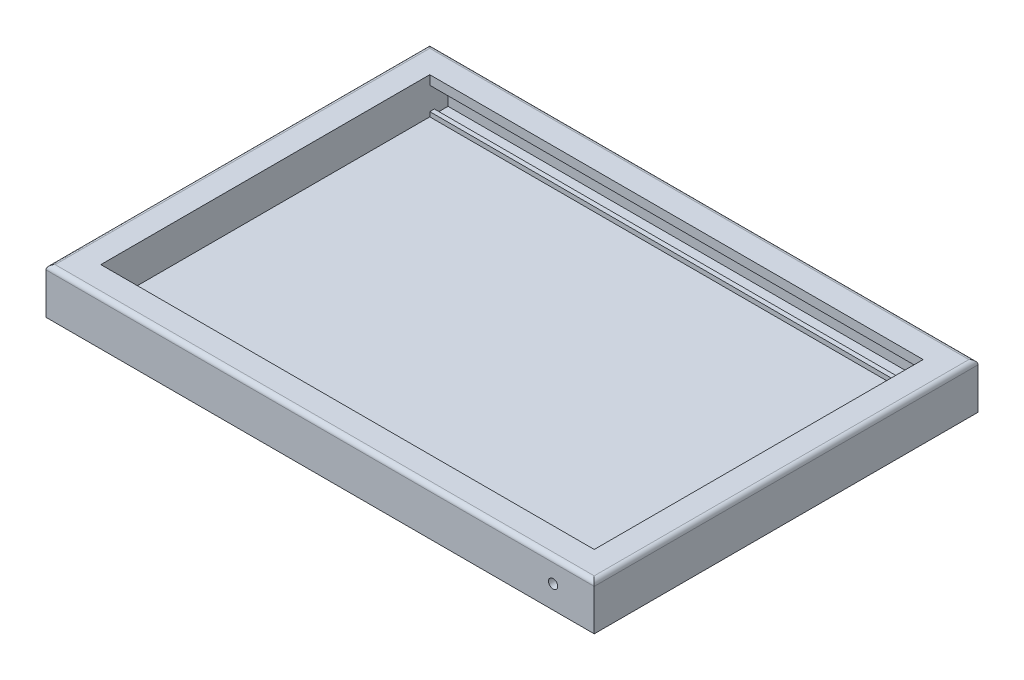
SolidWorks part; units mm, degrees
ref_plane "정면" through (0, 0, 0) normal (0, 0, 1) x (1, 0, 0)
ref_plane "윗면" through (0, 0, 0) normal (0, 1, 0) x (1, 0, 0)
ref_plane "우측면" through (0, 0, 0) normal (1, 0, 0) x (0, 0, -1)
sketch "스케치1" plane through (0, 0, 0) normal (0, 1, 0) x (1, 0, 0)
  line L1 (-571.2787, 18) -> (28.7213, 18)
  line L2 (-571.2787, 18) -> (-571.2787, -402)
  line L3 (-571.2787, -402) -> (28.7213, -402)
  line L4 (28.7213, 18) -> (28.7213, -402)
  dimension "D1" = 600
  dimension "D2" = 420
extrude "보스-돌출1" add sketch "스케치1" along normal blind 50
sketch "스케치2" plane through (0, 50, 0) normal (0, 1, 0) x (1, 0, 0)
  line L0 (28.7213, 18) -> (-571.2787, 18) construction
  line L1 (-541.2787, -12) -> (-1.2787, -12)
  line L2 (-541.2787, -12) -> (-541.2787, -372)
  line L3 (-541.2787, -372) -> (-1.2787, -372)
  line L4 (-1.2787, -12) -> (-1.2787, -372)
  line L5 (-571.2787, 18) -> (-571.2787, -402) construction
  line L6 (-571.2787, -402) -> (28.7213, -402) construction
  line L7 (28.7213, -402) -> (28.7213, 18) construction
  dimension "D1" = 30
  dimension "D2" = 30
  dimension "D3" = 30
  dimension "D4" = 30
extrude "컷-돌출1" cut sketch "스케치2" against normal blind 40
sketch "스케치3" plane through (0, 0, 12) normal (0, 0, 1) x (1, 0, 0)
  line L0 (-1.2787, 50) -> (-541.2787, 50) construction
  line L1 (-541.2787, 10) -> (-1.2787, 10)
  line L2 (-541.2787, 10) -> (-541.2787, 40)
  line L3 (-541.2787, 40) -> (-1.2787, 40)
  line L4 (-1.2787, 10) -> (-1.2787, 40)
  line L5 (-1.2787, 10) -> (-1.2787, 50) construction
  dimension "D1" = 10
extrude "컷-돌출2" cut sketch "스케치3" against normal blind 20
sketch "스케치4" plane through (0, 0, 372) normal (0, 0, -1) x (-1, 0, 0)
  line L0 (541.2787, 10) -> (541.2787, 50) construction
  line L1 (1.2787, 10) -> (541.2787, 10)
  line L2 (1.2787, 10) -> (1.2787, 40)
  line L3 (1.2787, 40) -> (541.2787, 40)
  line L4 (541.2787, 10) -> (541.2787, 40)
  line L5 (541.2787, 50) -> (1.2787, 50) construction
  dimension "D1" = 10
extrude "컷-돌출3" cut sketch "스케치4" against normal blind 20
sketch "스케치6" plane through (0, 50, 0) normal (0, 1, 0) x (1, 0, 0)
  line L0 (-1.2787, -12) -> (-541.2787, -12) construction
  line L1 (-1.2787, -12) -> (-541.2787, -12)
  line L2 (-1.2787, -12) -> (-1.2787, -7)
  line L3 (-1.2787, -7) -> (-541.2787, -7)
  line L4 (-541.2787, -12) -> (-541.2787, -7)
  dimension "D1" = 5
extrude "보스-돌출3" add sketch "스케치6" against normal blind 40
sketch "스케치7" plane through (0, 50, 0) normal (0, 1, 0) x (1, 0, 0)
  line L1 (-1.2787, -372) -> (-541.2787, -372)
  line L2 (-1.2787, -372) -> (-1.2787, -377)
  line L3 (-1.2787, -377) -> (-541.2787, -377)
  line L4 (-541.2787, -372) -> (-541.2787, -377)
  dimension "D1" = 5
extrude "보스-돌출4" add sketch "스케치7" against normal blind 40
sketch "스케치8" plane through (0, 0, 372) normal (0, 0, -1) x (-1, 0, 0)
  line L0 (1.2787, 10) -> (1.2787, 50) construction
  line L1 (1.2787, 45) -> (541.2787, 45)
  line L2 (1.2787, 45) -> (1.2787, 15)
  line L3 (1.2787, 15) -> (541.2787, 15)
  line L4 (541.2787, 45) -> (541.2787, 15)
  line L5 (541.2787, 50) -> (1.2787, 50) construction
  line L6 (1.2787, 10) -> (541.2787, 10) construction
  dimension "D1" = 5
  dimension "D2" = 5
  dimension "D3" = 540
extrude "컷-돌출4" cut sketch "스케치8" against normal blind 20
sketch "스케치9" plane through (0, 0, 12) normal (0, 0, 1) x (1, 0, 0)
  line L0 (-541.2787, 10) -> (-541.2787, 50) construction
  line L1 (-541.2787, 45) -> (-1.2787, 45)
  line L2 (-541.2787, 45) -> (-541.2787, 15)
  line L3 (-541.2787, 15) -> (-1.2787, 15)
  line L4 (-1.2787, 45) -> (-1.2787, 15)
  line L5 (-1.2787, 50) -> (-541.2787, 50) construction
  line L6 (-541.2787, 10) -> (-1.2787, 10) construction
  dimension "D1" = 5
  dimension "D2" = 5
  dimension "D3" = 540
extrude "컷-돌출5" cut sketch "스케치9" against normal blind 20
sketch "스케치11" plane through (0, 50, 0) normal (0, 1, 0) x (1, 0, 0)
  line L1 (-541.2787, -12) -> (-1.2787, -12)
  line L2 (-541.2787, -12) -> (-541.2787, -7)
  line L3 (-541.2787, -7) -> (-1.2787, -7)
  line L4 (-1.2787, -12) -> (-1.2787, -7)
  line L5 (-541.2787, -372) -> (-1.2787, -372)
  line L6 (-541.2787, -372) -> (-541.2787, -377)
  line L7 (-541.2787, -377) -> (-1.2787, -377)
  line L8 (-1.2787, -372) -> (-1.2787, -377)
  dimension "D1" = 5
  dimension "D2" = 540
  dimension "D3" = 5
  dimension "D4" = 540
extrude "보스-돌출6" add sketch "스케치11" against normal blind 10
sketch "스케치12" plane through (0, 0, 402) normal (0, 0, 1) x (1, 0, 0)
  line L0 (28.7213, 50) -> (28.7213, 0) construction
  circle A0 centre (-16.2787, 25) radius 5
  point P5 (28.7213, 25)
  dimension "D2" = 10
  dimension "D1" = 45
extrude "컷-돌출6" cut sketch "스케치12" against normal through all
fillet "필렛1" radius 5 4 edges at (28.7213, 50, 192) (-271.2787, 50, -18) (-571.2787, 50, 192) (-271.2787, 50, 402)
